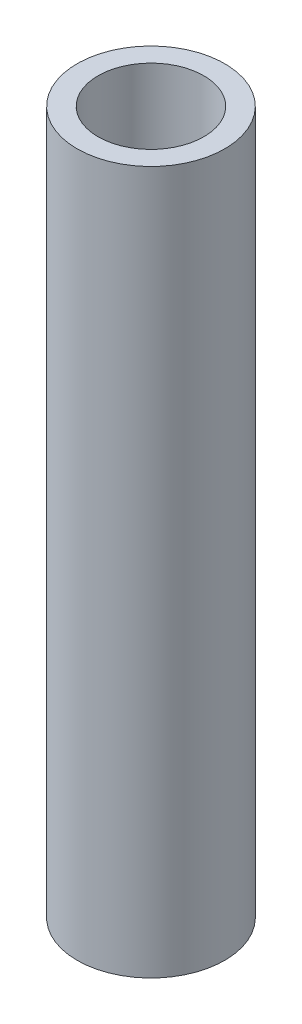
SolidWorks part; units mm, degrees
ref_plane "Front Plane" through (0, 0, 0) normal (0, 0, 1) x (1, 0, 0)
ref_plane "Top Plane" through (0, 0, 0) normal (0, 1, 0) x (1, 0, 0)
ref_plane "Right Plane" through (0, 0, 0) normal (1, 0, 0) x (0, 0, -1)
sketch "Sketch1" plane through (0, 0, 0) normal (0, 1, 0) x (1, 0, 0)
  circle A0 centre (0, 0) radius 7.6454
  circle A1 centre (0, 0) radius 10.668
  dimension "D1" = 21.336
  dimension "D2" = 15.2908
extrude "Boss-Extrude1" add sketch "Sketch1" along normal blind 101.6
